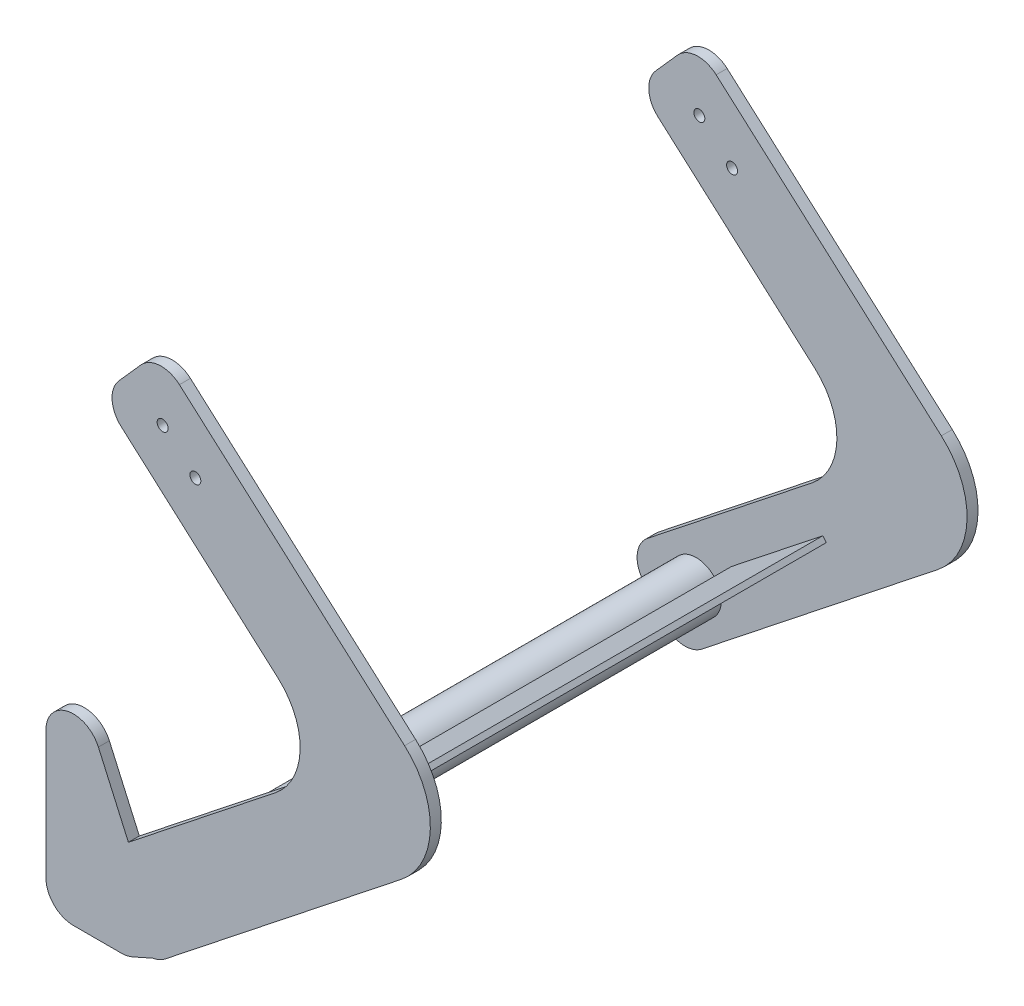
SolidWorks part; units mm, degrees
material "6061-T6 (SS)"
ref_plane "Front Plane" through (0, 0, 0) normal (0, 0, 1) x (1, 0, 0)
ref_plane "Top Plane" through (0, 0, 0) normal (0, 1, 0) x (1, 0, 0)
ref_plane "Right Plane" through (0, 0, 0) normal (1, 0, 0) x (0, 0, -1)
sketch "Sketch2" plane through (0, 0, 0) normal (0, 0, 1) x (1, 0, 0)
  line L0 (30.9438, 10.9723) -> (83.1595, -35.4232)
  line L1 (82.3883, -62.6529) -> (27.6305, -106.0188)
  line L2 (18.7102, -104.9832) -> (13.9793, -99.0096)
  line L5 (16.9178, 4.7469) -> (21.9791, 10.4431)
  line L6 (17.4469, -4.2178) -> (53.8227, -36.5389)
  line L7 (53.1617, -59.8786) -> (15.015, -90.0893)
  arc A0 (83.1595, -35.4232) -> (82.3883, -62.6529) centre (71.3497, -48.7145) cw
  arc A1 (53.8227, -36.5389) -> (53.1617, -59.8786) centre (43.7, -47.9315) cw
  arc A2 (27.6305, -106.0188) -> (18.7102, -104.9832) centre (23.6881, -101.0408) cw
  arc A3 (13.9793, -99.0096) -> (15.015, -90.0893) centre (18.9573, -95.0672) cw
  arc A4 (17.4469, -4.2178) -> (16.9178, 4.7469) centre (21.6647, 0.5291) cw
  arc A5 (30.9438, 10.9723) -> (21.9791, 10.4431) centre (26.726, 6.2254) ccw
  point P15 (22.6525, -109.9612)
  point P20 (12.7, 0)
  point P23 (26.1969, 15.19)
  dimension "D2" = 17.78
  dimension "D5" = 76.2
  dimension "D7" = 15.24
  dimension "D8" = 12.7
  dimension "D9" = 6.35
  dimension "D1" = 76.2
  dimension "D3" = 80
  dimension "D4" = 20.32
  dimension "D6" = 20.32
extrude "Boss-Extrude1" add sketch "Sketch2" along normal blind 2.54
sketch "Sketch3" plane through (0, 0, 2.54) normal (0, 0, 1) x (1, 0, 0)
  line L1 (53.1617, -59.8786) -> (15.015, -90.0893) construction
  line L2 (27.6305, -106.0188) -> (82.3883, -62.6529) construction
  line L3 (19.9929, -86.1469) -> (32.6085, -102.0764) construction
  line L4 (13.9793, -99.0096) -> (18.7102, -104.9832) construction
  circle A0 centre (26.3007, -94.1117) radius 5.8247
  point P8 (0, 0)
  point P9 (26.3007, -94.1117)
  dimension "D1" = 12.7
extrude "Boss-Extrude2" add sketch "Sketch3" against normal blind 63.5
mirror "Mirror1" about plane through (26.3007, -94.1117, -60.96) normal (0, 0, 1) of "Boss-Extrude1", "Boss-Extrude2"
sketch "Sketch4" plane through (0, 0, 0) normal (0, 0, -1) x (-1, 0, 0)
  line L0 (-26.3007, -94.1117) -> (-62.5151, -65.4313) construction
  line L1 (-53.1617, -59.8786) -> (-15.015, -90.0893) construction
  line L2 (-35.2476, -87.0261) -> (-34.4591, -86.0306)
  line L3 (-34.4591, -86.0306) -> (-55.6887, -69.2175)
  line L4 (-55.6887, -69.2175) -> (-56.4772, -70.2131)
  line L5 (-56.4772, -70.2131) -> (-35.2476, -87.0261)
  dimension "D1" = 1.27
extrude "Boss-Extrude3" add sketch "Sketch4" along normal blind 123.444
sketch "Sketch5" plane through (0, 0, 2.54) normal (0, 0, -1) x (-1, 0, 0)
  line L0 (-19.4484, 7.595) -> (-42.2012, -12.6216) construction
  line L1 (-21.9791, 10.4431) -> (-16.9178, 4.7469) construction
  circle A0 centre (-27.0434, 0.8466) radius 1.27
  circle A1 centre (-34.6385, -5.9019) radius 1.27
  point P4 (0, 0)
  point P9 (0, 0)
  dimension "D1" = 2.54
  dimension "D2" = 2.54
  dimension "D3" = 10.16
  dimension "D4" = 10.16
extrude "Cut-Extrude1" cut sketch "Sketch5" along normal through all
sketch "Sketch7" plane through (0, 0, 2.54) normal (0, 0, 1) x (1, 0, 0)
  line L0 (27.6305, -106.0188) -> (20.0566, -109.3861)
  line L1 (17.4769, -109.9337) -> (6.35, -109.9337)
  line L2 (0, -103.5837) -> (0, -73.7842)
  line L3 (12.1524, -71.2045) -> (27.6305, -106.0188)
  line L4 (0, 0) -> (0, -8.0638) construction
  arc A0 (20.0566, -109.3861) -> (17.4769, -109.9337) centre (17.4769, -103.5837) cw
  arc A1 (6.35, -109.9337) -> (0, -103.5837) centre (6.35, -103.5837) cw
  arc A2 (0, -73.7842) -> (12.1524, -71.2045) centre (6.35, -73.7842) cw
  dimension "D1" = 6.35
  dimension "D2" = 38.1
extrude "Boss-Extrude5" add sketch "Sketch7" against normal blind 2.54
